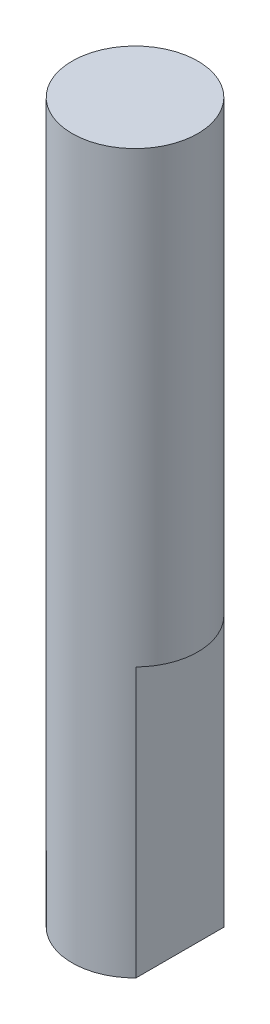
SolidWorks part; units mm, degrees
ref_plane "Front Plane" through (0, 0, 0) normal (0, 0, 1) x (1, 0, 0)
ref_plane "Top Plane" through (0, 0, 0) normal (0, 1, 0) x (1, 0, 0)
ref_plane "Right Plane" through (0, 0, 0) normal (1, 0, 0) x (0, 0, -1)
sketch "Sketch1" plane through (0, 0, 0) normal (0, 1, 0) x (1, 0, 0)
  circle A0 centre (0, 0) radius 7
  dimension "D1" = 14
extrude "Boss-Extrude1" add sketch "Sketch1" along normal blind 80
sketch "Sketch2" plane through (0, 0, 0) normal (0, -1, 0) x (1, 0, 0)
  line L0 (-5, 4.899) -> (-5, -4.899)
  line L1 (0, 7) -> (0, -7) construction
  line L2 (5, 4.899) -> (5, -4.899)
  circle A0 centre (0, 0) radius 7 construction
  arc A1 (5, -4.899) -> (5, 4.899) centre (0, 0) ccw
  circle A2 centre (0, 0) radius 7
  arc A3 (-5, 4.899) -> (-5, -4.899) centre (0, 0) ccw
  dimension "D1" = 5
  dimension "D2" = 0
extrude "Cut-Extrude1" cut sketch "Sketch2" against normal blind 30
